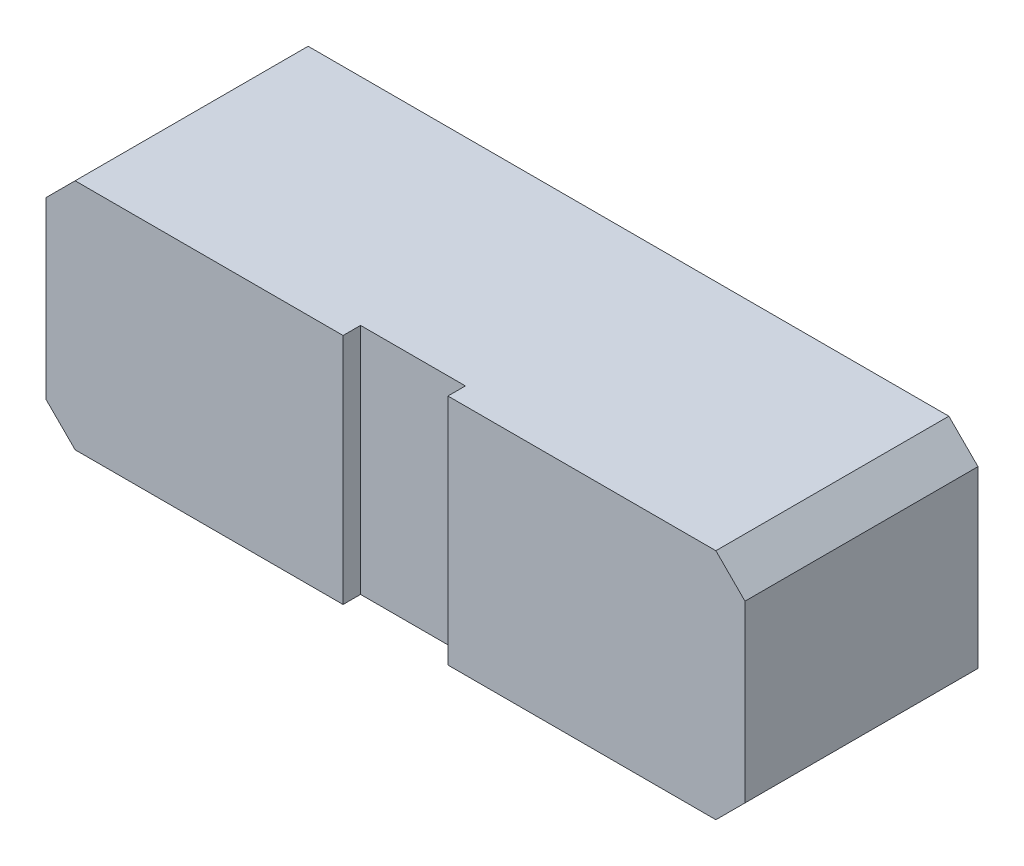
SolidWorks part; units mm, degrees
ref_plane "前视基准面" through (0, 0, 0) normal (0, 0, 1) x (1, 0, 0)
ref_plane "上视基准面" through (0, 0, 0) normal (0, 1, 0) x (1, 0, 0)
ref_plane "右视基准面" through (0, 0, 0) normal (1, 0, 0) x (0, 0, -1)
sketch "草图1" plane through (0, 0, 0) normal (0, 0, 1) x (1, 0, 0)
  line L1 (-60, 20) -> (60, 20)
  line L2 (-60, 20) -> (-60, -20)
  line L3 (-60, -20) -> (60, -20)
  line L4 (60, 20) -> (60, -20)
  line L5 (-60, 20) -> (60, -20) construction
  line L6 (-60, -20) -> (60, 20) construction
  point P0 (0, 0)
  dimension "D1" = 120
  dimension "D2" = 40
extrude "凸台-拉伸1" add sketch "草图1" along normal mid plane 40
sketch "草图2" plane through (0, 0, 20) normal (0, 0, 1) x (1, 0, 0)
  line L0 (-60, -20) -> (60, -20) construction
  line L1 (-9, 20) -> (9, 20)
  line L2 (-9, 20) -> (-9, -20)
  line L3 (-9, -20) -> (9, -20)
  line L4 (9, 20) -> (9, -20)
  line L5 (-9, 20) -> (9, -20) construction
  line L6 (-9, -20) -> (9, 20) construction
  point P0 (0, 0)
  dimension "D1" = 18
extrude "切除-拉伸1" cut sketch "草图2" against normal blind 3
chamfer "倒角1" distance 5 angle 45 4 edges at (60, 20, 0) (60, -20, 0) (-60, 20, 0) (-60, -20, 0)
equation "\"零件重量\"= \"SW-质量\""
